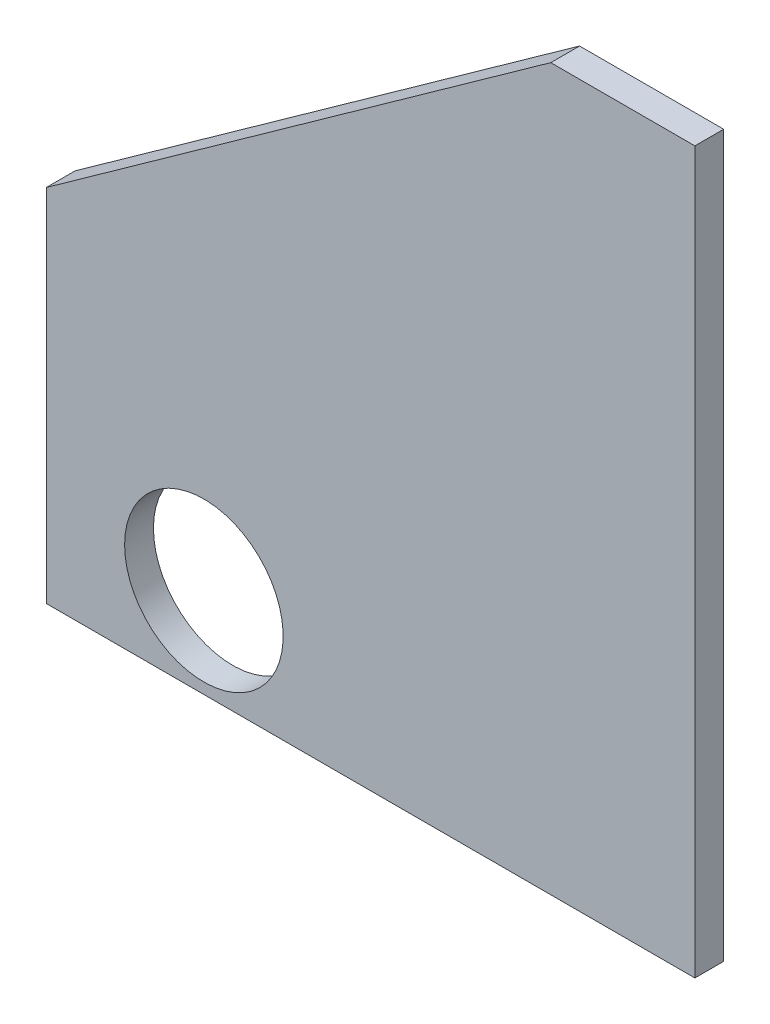
SolidWorks part; units mm, degrees
ref_plane "Front" through (0, 0, 0) normal (0, 0, 1) x (1, 0, 0)
ref_plane "Top" through (0, 0, 0) normal (0, 1, 0) x (1, 0, 0)
ref_plane "Right" through (0, 0, 0) normal (1, 0, 0) x (0, 0, -1)
sketch "Sketch1" plane through (0, 0, 0) normal (0, 0, 1) x (1, 0, 0)
  line L0 (0, 0) -> (90, 0)
  line L1 (90, 0) -> (90, 100)
  line L2 (90, 100) -> (70, 100)
  line L3 (70, 100) -> (0, 50)
  line L4 (0, 50) -> (0, 0)
  line L5 (94.412, 65.8232) -> (24.412, 15.8232) construction
  dimension "D2" = 90
  dimension "D3" = 50
  dimension "D4" = 20
  dimension "D5" = 100
  dimension "D1" = 42
extrude "Boss-Extrude1" add sketch "Sketch1" along normal blind 4
sketch "Sketch2" plane through (0, 0, 0) normal (0, 0, -1) x (-1, 0, 0)
  line L2 (-29.6996, 45.407) -> (-5.2876, 27.9699) construction
  line L3 (-36.0932, 36.4559) -> (-23.306, 54.3581) construction
  line L4 (-6.9079, 25.7015) -> (-3.6673, 30.2383) construction
  line L5 (-42.6176, 27.3218) -> (-18.2056, 9.8846) construction
  line L6 (0, 0) -> (-90, 0) construction
  circle A0 centre (-21.8671, 12.5) radius 11
  dimension "D1" = 22
  dimension "D2" = 22.225
  dimension "D3" = 12.5
extrude "Cut-Extrude1" cut sketch "Sketch2" against normal through all
